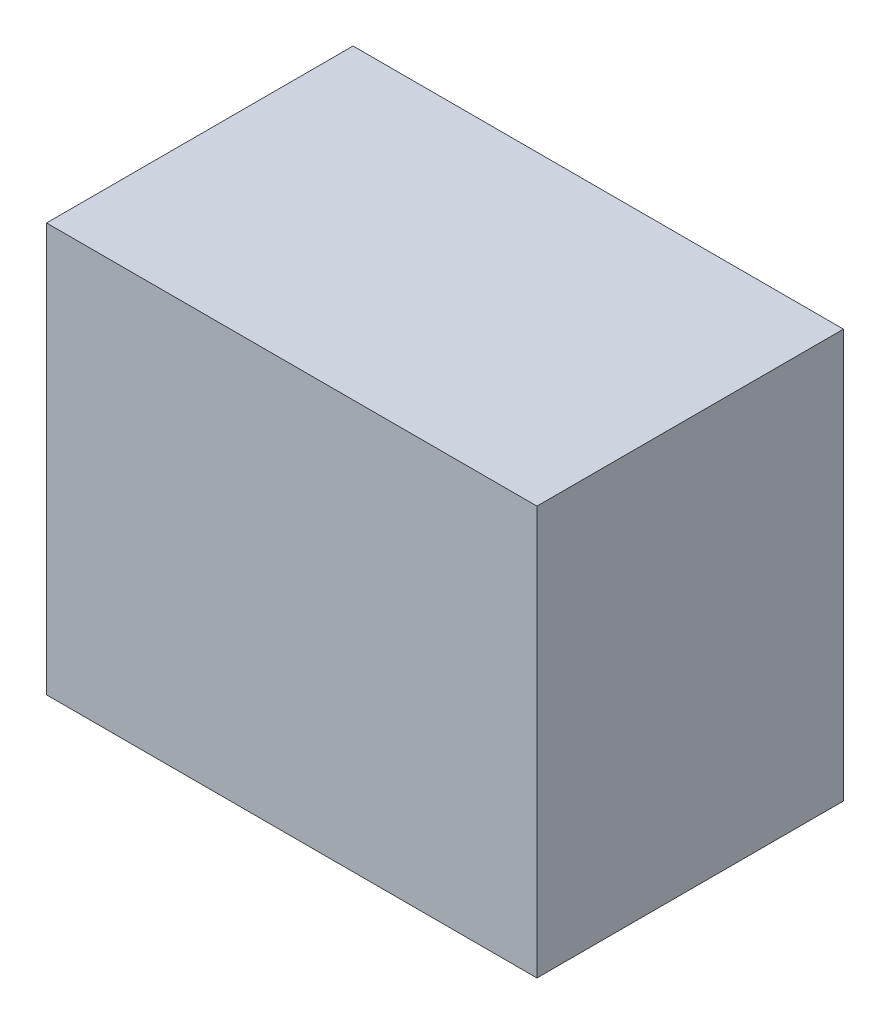
SolidWorks part; units mm, degrees
ref_plane "Front Plane" through (0, 0, 0) normal (0, 0, 1) x (1, 0, 0)
ref_plane "Top Plane" through (0, 0, 0) normal (0, 1, 0) x (1, 0, 0)
ref_plane "Right Plane" through (0, 0, 0) normal (1, 0, 0) x (0, 0, -1)
other "Configuration Table"
sketch "Sketch1" plane through (0, 0, 0) normal (0, 0, 1) x (1, 0, 0)
  line L1 (60, 180) -> (180, 180)
  line L2 (60, 180) -> (60, 280)
  line L3 (60, 280) -> (180, 280)
  line L4 (180, 180) -> (180, 280)
extrude "PACK_pano_plc_IO_1" add sketch "Sketch1" against normal blind 75 from offset 173 separate body
